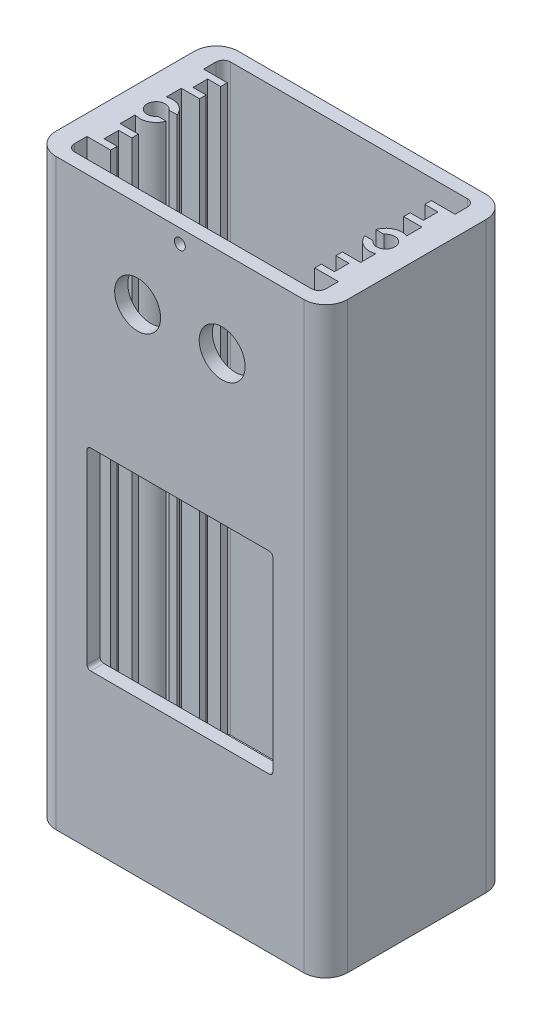
SolidWorks part; units mm, degrees
ref_plane "前视基准面" through (0, 0, 0) normal (0, 0, 1) x (1, 0, 0)
ref_plane "上视基准面" through (0, 0, 0) normal (0, 1, 0) x (1, 0, 0)
ref_plane "右视基准面" through (0, 0, 0) normal (1, 0, 0) x (0, 0, -1)
sketch "草图1" plane through (0, 0, 0) normal (0, 1, 0) x (1, 0, 0)
  line L0 (-26.6916, 8.1492) -> (61.0219, 8.1492) construction
  line L1 (313.6693, -188.884) -> (358.9997, -188.884) construction
  line L2 (-17.25, 8) -> (-14, 8)
  line L3 (-17, 12.5) -> (17, 12.5)
  line L4 (-20, 9.5) -> (-20, -9.5)
  line L5 (-17, -12.5) -> (17, -12.5)
  line L6 (20, 9.5) -> (20, -9.5)
  line L7 (-20, 12.5) -> (20, -12.5) construction
  line L8 (-20, -12.5) -> (20, 12.5) construction
  line L9 (-16.25, 10.7) -> (16.25, 10.7)
  line L10 (-17.25, 9.7) -> (-17.25, 8)
  line L11 (-16.25, -10.7) -> (16.25, -10.7)
  line L13 (-17.25, 10.7) -> (17.25, -10.7) construction
  line L14 (-17.25, -10.7) -> (17.25, 10.7) construction
  line L15 (-14, 8) -> (-14, 7.1)
  line L16 (-14, 7.1) -> (-15.8, 7.1)
  line L17 (-15.8, 7.1) -> (-15.8, 5.1)
  line L18 (-15.8, 5.1) -> (-14, 5.1)
  line L19 (-14, 5.1) -> (-14, 4.2)
  line L20 (-14, 4.2) -> (-16.5, 4.2)
  line L21 (-16.5, 4.2) -> (-16.5, 2.1213)
  line L22 (-16.5, -4.2) -> (-14, -4.2)
  line L23 (-14, -4.2) -> (-14, -5.1)
  line L24 (-14, -5.1) -> (-15.8, -5.1)
  line L25 (-15.8, -5.1) -> (-15.8, -7.1)
  line L26 (-15.8, -7.1) -> (-14, -7.1)
  line L27 (-14, -7.1) -> (-14, -8)
  line L28 (-14, -8) -> (-17.25, -8)
  line L29 (-15.75, 0) -> (9.2222, 0) construction
  line L30 (-14.75, 0.75) -> (-13.6287, 0.75)
  line L31 (-17.25, -8) -> (-17.25, -9.7)
  line L32 (-13.6287, -0.75) -> (-14.75, -0.75)
  line L33 (-16.5, -2.1213) -> (-16.5, -4.2)
  line L34 (0, 16.2022) -> (0, -15.1433) construction
  line L35 (17.25, 9.7) -> (17.25, 8)
  line L36 (17.25, 8) -> (14, 8)
  line L37 (14, 8) -> (14, 7.1)
  line L38 (14, 7.1) -> (15.8, 7.1)
  line L39 (15.8, 7.1) -> (15.8, 5.1)
  line L40 (15.8, 5.1) -> (14, 5.1)
  line L41 (14, 5.1) -> (14, 4.2)
  line L42 (14, 4.2) -> (16.5, 4.2)
  line L43 (16.5, 4.2) -> (16.5, 2.1213)
  line L44 (14.75, 0.75) -> (13.6287, 0.75)
  line L45 (13.6287, -0.75) -> (14.75, -0.75)
  line L46 (16.5, -2.1213) -> (16.5, -4.2)
  line L47 (16.5, -4.2) -> (14, -4.2)
  line L48 (14, -4.2) -> (14, -5.1)
  line L49 (14, -5.1) -> (15.8, -5.1)
  line L50 (15.8, -5.1) -> (15.8, -7.1)
  line L51 (15.8, -7.1) -> (14, -7.1)
  line L52 (14, -7.1) -> (14, -8)
  line L53 (14, -8) -> (17.25, -8)
  line L54 (17.25, -8) -> (17.25, -9.7)
  arc A0 (20, 9.5) -> (17, 12.5) centre (17, 9.5) ccw
  arc A1 (17, -12.5) -> (20, -9.5) centre (17, -9.5) ccw
  arc A2 (-17, -12.5) -> (-20, -9.5) centre (-17, -9.5) cw
  arc A3 (-20, 9.5) -> (-17, 12.5) centre (-17, 9.5) cw
  arc A4 (-17.25, -9.7) -> (-16.25, -10.7) centre (-16.25, -9.7) ccw
  arc A7 (-17.25, 9.7) -> (-16.25, 10.7) centre (-16.25, 9.7) cw
  arc A8 (-16.5, -2.1213) -> (-13.6287, -0.75) centre (-15.75, 0) ccw
  arc A9 (-14.75, 0.75) -> (-14.75, -0.75) centre (-15.75, 0) ccw
  arc A10 (-13.6287, 0.75) -> (-16.5, 2.1213) centre (-15.75, 0) ccw
  arc A11 (17.25, 9.7) -> (16.25, 10.7) centre (16.25, 9.7) ccw
  arc A12 (13.6287, 0.75) -> (16.5, 2.1213) centre (15.75, 0) cw
  arc A13 (14.75, 0.75) -> (14.75, -0.75) centre (15.75, 0) cw
  arc A14 (16.5, -2.1213) -> (13.6287, -0.75) centre (15.75, 0) cw
  arc A15 (17.25, -9.7) -> (16.25, -10.7) centre (16.25, -9.7) cw
  point P4 (0, 0)
  point P12 (0, 0)
  point P33 (0, 10.7)
  point P91 (0, -10.7)
  dimension "D5" = 3
  dimension "D6" = 1
  dimension "D19" = 4.5
  dimension "D20" = 2.5
  dimension "D1" = 25
  dimension "D2" = 40
  dimension "D3" = 34.5
  dimension "D4" = 21.4
  dimension "D7" = 3.5
  dimension "D8" = 4.2
  dimension "D9" = 2
  dimension "D10" = 0.9
  dimension "D11" = 6
  dimension "D12" = 3.8
  dimension "D13" = 3.8
  dimension "D14" = 2
  dimension "D15" = 16
  dimension "D16" = 0.9
  dimension "D17" = 8
  dimension "D18" = 15.75
  dimension "D21" = 1.5
  dimension "D22" = 0.75
extrude "凸台-拉伸1" add sketch "草图1" along normal blind 80 contours L9 A11 L35 L36 L37 L38 L39 L40 L41 L42 L43 A12 L44 A13 L45 A14 L46 L47 L48 L49 L50 L51 L52 L53 L54 A15 L11 A4 L31 L28 L27 L26 L25 L24 L23 L22 L33 A8 L32 A9 L30 A10 L21 L20 L19 L18 L17 L16 L15 L2 L10 A7
sketch "草图2" plane through (0, 0, 12.5) normal (0, 0, 1) x (1, 0, 0)
  line L0 (0, 0) -> (0, 110.3188) construction
  line L1 (-14.4, 50.3) -> (14.4, 50.3) construction
  line L2 (-14.9, 49.8) -> (-14.9, 14) construction
  line L3 (-14.4, 13.5) -> (14.4, 13.5) construction
  line L4 (14.9, 49.8) -> (14.9, 14) construction
  line L5 (-14.9, 50.3) -> (14.9, 13.5) construction
  line L6 (-14.9, 13.5) -> (14.9, 50.3) construction
  line L8 (-17, 0) -> (17, 0) construction
  line L9 (-12.25, 47.74) -> (12.25, 47.74)
  line L10 (-12.75, 47.24) -> (-12.75, 21.74)
  line L11 (-12.25, 21.24) -> (12.25, 21.24)
  line L12 (12.75, 47.24) -> (12.75, 21.74)
  line L13 (-12.75, 47.74) -> (12.75, 21.24) construction
  line L14 (-12.75, 21.24) -> (12.75, 47.74) construction
  arc A0 (-14.9, 14) -> (-14.4, 13.5) centre (-14.4, 14) ccw construction
  arc A1 (14.9, 14) -> (14.4, 13.5) centre (14.4, 14) cw construction
  arc A2 (14.4, 50.3) -> (14.9, 49.8) centre (14.4, 49.8) cw construction
  arc A3 (-14.4, 50.3) -> (-14.9, 49.8) centre (-14.4, 49.8) ccw construction
  arc A4 (-12.75, 21.74) -> (-12.25, 21.24) centre (-12.25, 21.74) ccw
  arc A5 (12.25, 21.24) -> (12.75, 21.74) centre (12.25, 21.74) ccw
  arc A6 (12.75, 47.24) -> (12.25, 47.74) centre (12.25, 47.24) ccw
  arc A7 (-12.75, 47.24) -> (-12.25, 47.74) centre (-12.25, 47.24) cw
  point P0 (0, 31.9)
  point P22 (0, 34.49)
  point P27 (0, 35.8917)
  dimension "D4" = 0.5
  dimension "D8" = 0.5
  dimension "D1" = 29.8
  dimension "D2" = 36.8
  dimension "D3" = 13.5
  dimension "D5" = 25.5
  dimension "D6" = 26.5
  dimension "D7" = 2.56
extrude "切除-拉伸1" cut sketch "草图2" against normal up to next
sketch "草图3" plane through (0, 0, 12.5) normal (0, 0, 1) x (1, 0, 0)
  line L0 (-17, 0) -> (17, 0) construction
  line L3 (20, 80) -> (20, 0) construction
  line L4 (-20, 80) -> (-20, 0) construction
  circle A0 centre (-5.8, 68) radius 3.15
  circle A1 centre (5.8, 68) radius 3.15
  dimension "D3" = 14.2
  dimension "D4" = 6.3
  dimension "D1" = 68
  dimension "D2" = 14.2
extrude "切除-拉伸2" cut sketch "草图3" against normal up to next
sketch "草图4" plane through (0, 0, 12.5) normal (0, 0, 1) x (1, 0, 0)
  line L0 (-17, 80) -> (17, 80) construction
  circle A0 centre (0, 78.1) radius 0.75
  dimension "D2" = 1.5
  dimension "D1" = 1.9
extrude "切除-拉伸3" cut sketch "草图4" against normal up to next
